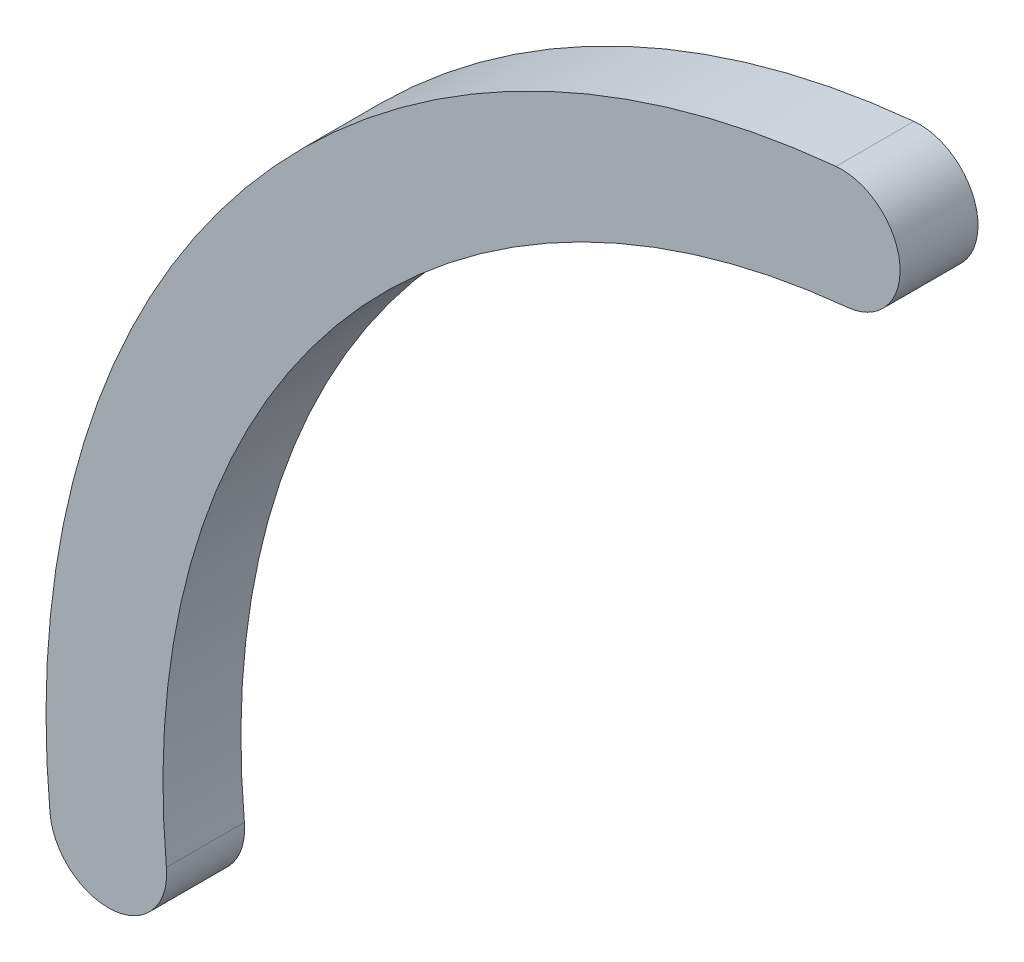
SolidWorks part; units mm, degrees
ref_plane "Front Plane" through (0, 0, 0) normal (0, 0, 1) x (1, 0, 0)
ref_plane "Top Plane" through (0, 0, 0) normal (0, 1, 0) x (1, 0, 0)
ref_plane "Right Plane" through (0, 0, 0) normal (1, 0, 0) x (0, 0, -1)
sketch "Sketch2" plane through (0, 0, -8.3603) normal (0, 0, 1) x (1, 0, 0)
  arc A0 (-46.9726, 79.2618) -> (-46.6082, 75.4693) centre (-46.7904, 77.3656) cw
  arc A1 (-68.7891, 48.5727) -> (-46.6082, 75.4693) centre (-44.2504, 50.9306) cw
  arc A2 (-72.5817, 48.2083) -> (-46.9726, 79.2618) centre (-44.2504, 50.9306) cw
  arc A3 (-72.5817, 48.2083) -> (-68.7891, 48.5727) centre (-70.6854, 48.3905) ccw
extrude "Boss-Extrude1" add sketch "Sketch2" along normal blind 2.54
